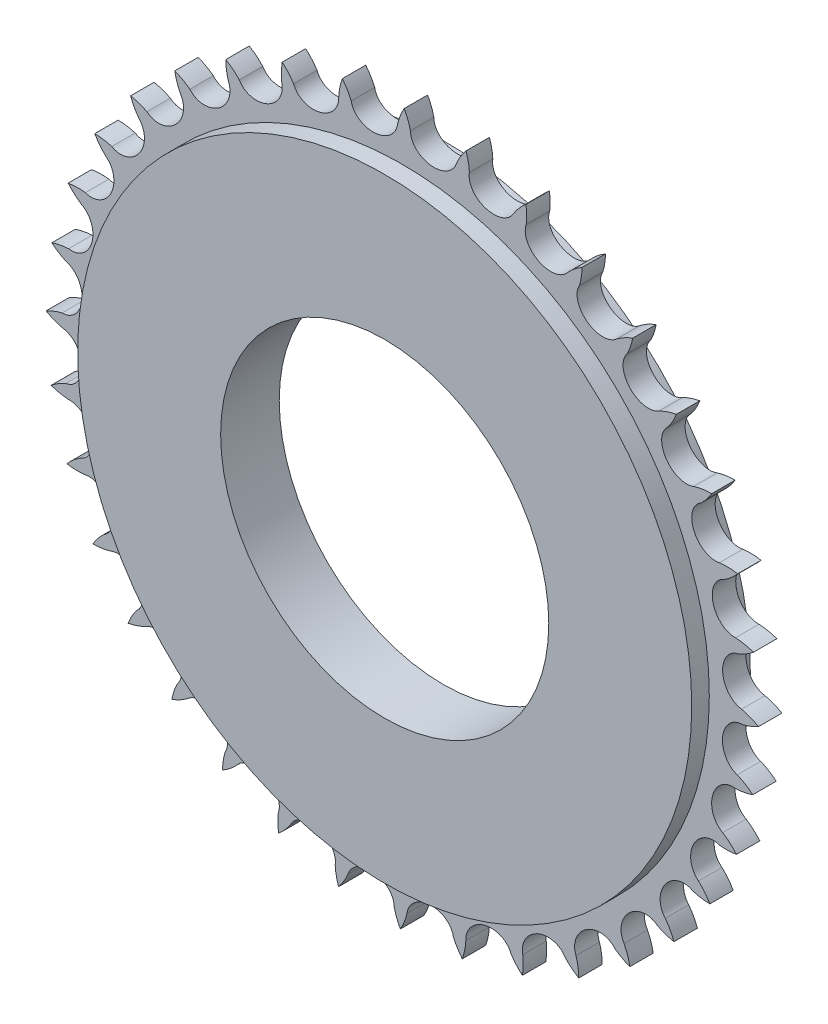
SolidWorks part; units mm, degrees
ref_plane "Front Plane" through (0, 0, 0) normal (0, 0, 1) x (1, 0, 0)
ref_plane "Top Plane" through (0, 0, 0) normal (0, 1, 0) x (1, 0, 0)
ref_plane "Right Plane" through (0, 0, 0) normal (1, 0, 0) x (0, 0, -1)
sketch "Sketch1" plane through (0, 0, 0) normal (0, 0, 1) x (1, 0, 0)
  arc A199 (14.3129, 71.1684) -> (13.5964, 74.7739) centre (1.3321, 70.4626) ccw
  arc A207 (1.7372, 72.5726) -> (0.4055, 75.9989) centre (-10.9239, 69.6235) ccw
  arc A208 (-1.0123, 72.3764) -> (0.4055, 75.9989) centre (11.6661, 69.503) cw
  arc A209 (11.5711, 71.4527) -> (13.5964, 74.7739) centre (23.5579, 66.4212) cw
  arc A210 (26.4537, 67.6018) -> (26.3742, 71.2769) centre (13.5475, 69.1608) ccw
  arc A211 (23.8029, 68.3578) -> (26.3742, 71.2769) centre (34.734, 61.3214) cw
  arc A212 (37.7908, 61.9811) -> (38.3506, 65.6143) centre (25.3514, 65.7576) ccw
  arc A213 (35.3115, 63.186) -> (38.3506, 65.6143) centre (44.8546, 54.3583) cw
  arc A214 (47.9795, 54.4772) -> (49.1618, 57.9579) centre (36.3849, 60.3564) ccw
  arc A215 (45.7472, 56.0943) -> (49.1618, 57.9579) centre (53.6124, 45.7435) cw
  arc A216 (56.7105, 45.318) -> (58.4792, 48.5406) centre (46.3129, 53.1213) ccw
  arc A217 (54.7929, 47.2982) -> (58.4792, 48.5406) centre (60.7412, 35.7389) cw
  arc A218 (63.7183, 34.7818) -> (66.0197, 37.6483) centre (54.8338, 44.2721) ccw
  arc A219 (62.1737, 37.0649) -> (66.0197, 37.6483) centre (66.0244, 24.6483) cw
  arc A220 (68.7901, 23.1889) -> (71.5543, 25.6122) centre (61.6885, 34.0777) ccw
  arc A221 (67.6654, 25.7055) -> (71.5543, 25.6122) centre (69.3015, 12.8088) cw
  arc A222 (71.7717, 10.8913) -> (74.9147, 12.7978) centre (66.6688, 22.8479) ccw
  arc A223 (71.1011, 13.565) -> (74.9147, 12.7978) centre (70.4728, 0.5802) cw
  arc A224 (72.5726, -1.7372) -> (75.9989, -0.4055) centre (69.6235, 10.9239) ccw
  arc A225 (72.3764, 1.0123) -> (75.9989, -0.4055) centre (69.503, -11.6661) cw
  arc A226 (71.1684, -14.3129) -> (74.7739, -13.5964) centre (70.4626, -1.3321) ccw
  arc A227 (71.4527, -11.5711) -> (74.7739, -13.5964) centre (66.4212, -23.5579) cw
  arc A228 (67.6018, -26.4537) -> (71.2769, -26.3742) centre (69.1608, -13.5475) ccw
  arc A229 (68.3578, -23.8029) -> (71.2769, -26.3742) centre (61.3214, -34.734) cw
  arc A230 (61.9811, -37.7908) -> (65.6143, -38.3506) centre (65.7576, -25.3514) ccw
  arc A231 (63.186, -35.3115) -> (65.6143, -38.3506) centre (54.3583, -44.8546) cw
  arc A232 (54.4772, -47.9795) -> (57.9579, -49.1618) centre (60.3564, -36.3849) ccw
  arc A233 (56.0943, -45.7472) -> (57.9579, -49.1618) centre (45.7435, -53.6124) cw
  arc A234 (45.318, -56.7105) -> (48.5406, -58.4792) centre (53.1213, -46.3129) ccw
  arc A235 (47.2982, -54.7929) -> (48.5406, -58.4792) centre (35.7389, -60.7412) cw
  arc A236 (34.7818, -63.7183) -> (37.6483, -66.0197) centre (44.2721, -54.8338) ccw
  arc A237 (37.0649, -62.1737) -> (37.6483, -66.0197) centre (24.6483, -66.0244) cw
  arc A238 (23.1889, -68.7901) -> (25.6122, -71.5543) centre (34.0777, -61.6885) ccw
  arc A239 (25.7055, -67.6654) -> (25.6122, -71.5543) centre (12.8088, -69.3015) cw
  arc A240 (10.8913, -71.7717) -> (12.7978, -74.9147) centre (22.8479, -66.6688) ccw
  arc A241 (13.565, -71.1011) -> (12.7978, -74.9147) centre (0.5802, -70.4728) cw
  arc A242 (-1.7372, -72.5726) -> (-0.4055, -75.9989) centre (10.9239, -69.6235) ccw
  arc A243 (1.0123, -72.3764) -> (-0.4055, -75.9989) centre (-11.6661, -69.503) cw
  arc A244 (-14.3129, -71.1684) -> (-13.5964, -74.7739) centre (-1.3321, -70.4626) ccw
  arc A245 (-11.5711, -71.4527) -> (-13.5964, -74.7739) centre (-23.5579, -66.4212) cw
  arc A246 (-26.4537, -67.6018) -> (-26.3742, -71.2769) centre (-13.5475, -69.1608) ccw
  arc A247 (-23.8029, -68.3578) -> (-26.3742, -71.2769) centre (-34.734, -61.3214) cw
  arc A248 (-37.7908, -61.9811) -> (-38.3506, -65.6143) centre (-25.3514, -65.7576) ccw
  arc A249 (-35.3115, -63.186) -> (-38.3506, -65.6143) centre (-44.8546, -54.3583) cw
  arc A250 (-47.9795, -54.4772) -> (-49.1618, -57.9579) centre (-36.3849, -60.3564) ccw
  arc A251 (-45.7472, -56.0943) -> (-49.1618, -57.9579) centre (-53.6124, -45.7435) cw
  arc A252 (-56.7105, -45.318) -> (-58.4792, -48.5406) centre (-46.3129, -53.1213) ccw
  arc A253 (-54.7929, -47.2982) -> (-58.4792, -48.5406) centre (-60.7412, -35.7389) cw
  arc A254 (-63.7183, -34.7818) -> (-66.0197, -37.6483) centre (-54.8338, -44.2721) ccw
  arc A255 (-62.1737, -37.0649) -> (-66.0197, -37.6483) centre (-66.0244, -24.6483) cw
  arc A256 (-68.7901, -23.1889) -> (-71.5543, -25.6122) centre (-61.6885, -34.0777) ccw
  arc A257 (-67.6654, -25.7055) -> (-71.5543, -25.6122) centre (-69.3015, -12.8088) cw
  arc A258 (-71.7717, -10.8913) -> (-74.9147, -12.7978) centre (-66.6688, -22.8479) ccw
  arc A259 (-71.1011, -13.565) -> (-74.9147, -12.7978) centre (-70.4728, -0.5802) cw
  arc A260 (-72.5726, 1.7372) -> (-75.9989, 0.4055) centre (-69.6235, -10.9239) ccw
  arc A261 (-72.3764, -1.0123) -> (-75.9989, 0.4055) centre (-69.503, 11.6661) cw
  arc A262 (-71.1684, 14.3129) -> (-74.7739, 13.5964) centre (-70.4626, 1.3321) ccw
  arc A263 (-71.4527, 11.5711) -> (-74.7739, 13.5964) centre (-66.4212, 23.5579) cw
  arc A264 (-67.6018, 26.4537) -> (-71.2769, 26.3742) centre (-69.1608, 13.5475) ccw
  arc A265 (-68.3578, 23.8029) -> (-71.2769, 26.3742) centre (-61.3214, 34.734) cw
  arc A266 (-61.9811, 37.7908) -> (-65.6143, 38.3506) centre (-65.7576, 25.3514) ccw
  arc A267 (-63.186, 35.3115) -> (-65.6143, 38.3506) centre (-54.3583, 44.8546) cw
  arc A268 (-54.4772, 47.9795) -> (-57.9579, 49.1618) centre (-60.3564, 36.3849) ccw
  arc A269 (-56.0943, 45.7472) -> (-57.9579, 49.1618) centre (-45.7435, 53.6124) cw
  arc A270 (-45.318, 56.7105) -> (-48.5406, 58.4792) centre (-53.1213, 46.3129) ccw
  arc A271 (-47.2982, 54.7929) -> (-48.5406, 58.4792) centre (-35.7389, 60.7412) cw
  arc A272 (-34.7818, 63.7183) -> (-37.6483, 66.0197) centre (-44.2721, 54.8338) ccw
  arc A273 (-37.0649, 62.1737) -> (-37.6483, 66.0197) centre (-24.6483, 66.0244) cw
  arc A274 (-23.1889, 68.7901) -> (-25.6122, 71.5543) centre (-34.0777, 61.6885) ccw
  arc A275 (-25.7055, 67.6654) -> (-25.6122, 71.5543) centre (-12.8088, 69.3015) cw
  arc A276 (-10.8913, 71.7717) -> (-12.7978, 74.9147) centre (-22.8479, 66.6688) ccw
  arc A277 (-13.565, 71.1011) -> (-12.7978, 74.9147) centre (-0.5802, 70.4728) cw
  circle A278 centre (0, 0) radius 35
  ellipse E0 centre (19.2322, 70.2739) end of major axis (14.3129, 71.1684) minor radius 4.25 (14.3129, 71.1684) -> (18.4719, 66.0925) ccw
  ellipse E1 centre (6.7371, 72.5459) end of major axis (11.7371, 72.5192) minor radius 4.25 (1.7372, 72.5726) -> (6.7145, 68.296) ccw
  ellipse E2 centre (6.7371, 72.5459) end of major axis (11.7371, 72.5192) minor radius 4.25 (6.7145, 68.296) -> (11.5711, 71.4527) ccw
  ellipse E3 centre (31.143, 65.8666) end of major axis (35.8323, 64.1315) minor radius 4.25 (26.4537, 67.6018) -> (29.6681, 61.8808) ccw
  ellipse E4 centre (19.2322, 70.2739) end of major axis (24.1516, 69.3794) minor radius 4.25 (18.4719, 66.0925) -> (23.8029, 68.3578) ccw
  ellipse E5 centre (-5.9627, 72.6137) end of major axis (-1.0341, 73.4556) minor radius 4.25 (-5.247, 68.4244) -> (-1.0123, 72.3764) ccw
  ellipse E6 centre (42.1075, 59.458) end of major axis (37.7908, 61.9811) minor radius 4.25 (37.7908, 61.9811) -> (39.9629, 55.7888) ccw
  ellipse E7 centre (31.143, 65.8666) end of major axis (35.8323, 64.1315) minor radius 4.25 (29.6681, 61.8808) -> (35.3115, 63.186) ccw
  ellipse E8 centre (51.7926, 51.2429) end of major axis (47.9795, 54.4772) minor radius 4.25 (47.9795, 54.4772) -> (49.0434, 48.0018) ccw
  ellipse E9 centre (42.1075, 59.458) end of major axis (46.4242, 56.935) minor radius 4.25 (39.9629, 55.7888) -> (45.7472, 56.0943) ccw
  ellipse E10 centre (59.9039, 41.4707) end of major axis (63.0974, 37.6234) minor radius 4.25 (56.7105, 45.318) -> (56.6337, 38.7562) ccw
  ellipse E11 centre (51.7926, 51.2429) end of major axis (55.6056, 48.0085) minor radius 4.25 (49.0434, 48.0018) -> (54.7929, 47.2982) ccw
  ellipse E12 centre (66.1952, 30.4384) end of major axis (63.7183, 34.7818) minor radius 4.25 (63.7183, 34.7818) -> (62.5033, 28.3331) ccw
  ellipse E13 centre (59.9039, 41.4707) end of major axis (63.0974, 37.6234) minor radius 4.25 (56.6337, 38.7562) -> (62.1737, 37.0649) ccw
  ellipse E14 centre (70.4751, 18.4813) end of major axis (68.7901, 23.1889) minor radius 4.25 (68.7901, 23.1889) -> (66.4737, 17.0491) ccw
  ellipse E15 centre (66.1952, 30.4384) end of major axis (68.672, 26.095) minor radius 4.25 (62.5033, 28.3331) -> (67.6654, 25.7055) ccw
  ellipse E16 centre (72.6137, 5.9627) end of major axis (73.4556, 1.0341) minor radius 4.25 (71.7717, 10.8913) -> (68.4244, 5.247) ccw
  ellipse E17 centre (70.4751, 18.4813) end of major axis (72.1601, 13.7738) minor radius 4.25 (66.4737, 17.0491) -> (71.1011, 13.565) ccw
  ellipse E18 centre (72.5459, -6.7371) end of major axis (72.5726, -1.7372) minor radius 4.25 (72.5726, -1.7372) -> (68.296, -6.7145) ccw
  ellipse E19 centre (72.6137, 5.9627) end of major axis (73.4556, 1.0341) minor radius 4.25 (68.4244, 5.247) -> (72.3764, 1.0123) ccw
  ellipse E20 centre (70.2739, -19.2322) end of major axis (71.1684, -14.3129) minor radius 4.25 (71.1684, -14.3129) -> (66.0925, -18.4719) ccw
  ellipse E21 centre (72.5459, -6.7371) end of major axis (72.5192, -11.7371) minor radius 4.25 (68.296, -6.7145) -> (71.4527, -11.5711) ccw
  ellipse E22 centre (65.8666, -31.143) end of major axis (67.6018, -26.4537) minor radius 4.25 (67.6018, -26.4537) -> (61.8808, -29.6681) ccw
  ellipse E23 centre (70.2739, -19.2322) end of major axis (69.3794, -24.1516) minor radius 4.25 (66.0925, -18.4719) -> (68.3578, -23.8029) ccw
  ellipse E24 centre (59.458, -42.1075) end of major axis (61.9811, -37.7908) minor radius 4.25 (61.9811, -37.7908) -> (55.7888, -39.9629) ccw
  ellipse E25 centre (65.8666, -31.143) end of major axis (64.1315, -35.8323) minor radius 4.25 (61.8808, -29.6681) -> (63.186, -35.3115) ccw
  ellipse E26 centre (51.2429, -51.7926) end of major axis (54.4772, -47.9795) minor radius 4.25 (54.4772, -47.9795) -> (48.0018, -49.0434) ccw
  ellipse E27 centre (59.458, -42.1075) end of major axis (56.935, -46.4242) minor radius 4.25 (55.7888, -39.9629) -> (56.0943, -45.7472) ccw
  ellipse E28 centre (41.4707, -59.9039) end of major axis (37.6234, -63.0974) minor radius 4.25 (45.318, -56.7105) -> (38.7562, -56.6337) ccw
  ellipse E29 centre (51.2429, -51.7926) end of major axis (48.0085, -55.6056) minor radius 4.25 (48.0018, -49.0434) -> (47.2982, -54.7929) ccw
  ellipse E30 centre (30.4384, -66.1952) end of major axis (26.095, -68.672) minor radius 4.25 (34.7818, -63.7183) -> (28.3331, -62.5033) ccw
  ellipse E31 centre (41.4707, -59.9039) end of major axis (37.6234, -63.0974) minor radius 4.25 (38.7562, -56.6337) -> (37.0649, -62.1737) ccw
  ellipse E32 centre (18.4813, -70.4751) end of major axis (23.1889, -68.7901) minor radius 4.25 (23.1889, -68.7901) -> (17.0491, -66.4737) ccw
  ellipse E33 centre (30.4384, -66.1952) end of major axis (34.7818, -63.7183) minor radius 4.25 (28.3331, -62.5033) -> (25.7055, -67.6654) ccw
  ellipse E34 centre (5.9627, -72.6137) end of major axis (1.0341, -73.4556) minor radius 4.25 (10.8913, -71.7717) -> (5.247, -68.4244) ccw
  ellipse E35 centre (18.4813, -70.4751) end of major axis (13.7738, -72.1601) minor radius 4.25 (17.0491, -66.4737) -> (13.565, -71.1011) ccw
  ellipse E36 centre (-6.7371, -72.5459) end of major axis (-1.7372, -72.5726) minor radius 4.25 (-1.7372, -72.5726) -> (-6.7145, -68.296) ccw
  ellipse E37 centre (5.9627, -72.6137) end of major axis (1.0341, -73.4556) minor radius 4.25 (5.247, -68.4244) -> (1.0123, -72.3764) ccw
  ellipse E38 centre (-19.2322, -70.2739) end of major axis (-14.3129, -71.1684) minor radius 4.25 (-14.3129, -71.1684) -> (-18.4719, -66.0925) ccw
  ellipse E39 centre (-6.7371, -72.5459) end of major axis (-11.7371, -72.5192) minor radius 4.25 (-6.7145, -68.296) -> (-11.5711, -71.4527) ccw
  ellipse E40 centre (-31.143, -65.8666) end of major axis (-26.4537, -67.6018) minor radius 4.25 (-26.4537, -67.6018) -> (-29.6681, -61.8808) ccw
  ellipse E41 centre (-19.2322, -70.2739) end of major axis (-24.1516, -69.3794) minor radius 4.25 (-18.4719, -66.0925) -> (-23.8029, -68.3578) ccw
  ellipse E42 centre (-42.1075, -59.458) end of major axis (-37.7908, -61.9811) minor radius 4.25 (-37.7908, -61.9811) -> (-39.9629, -55.7888) ccw
  ellipse E43 centre (-31.143, -65.8666) end of major axis (-35.8323, -64.1315) minor radius 4.25 (-29.6681, -61.8808) -> (-35.3115, -63.186) ccw
  ellipse E44 centre (-51.7926, -51.2429) end of major axis (-47.9795, -54.4772) minor radius 4.25 (-47.9795, -54.4772) -> (-49.0434, -48.0018) ccw
  ellipse E45 centre (-42.1075, -59.458) end of major axis (-46.4242, -56.935) minor radius 4.25 (-39.9629, -55.7888) -> (-45.7472, -56.0943) ccw
  ellipse E46 centre (-59.9039, -41.4707) end of major axis (-63.0974, -37.6234) minor radius 4.25 (-56.7105, -45.318) -> (-56.6337, -38.7562) ccw
  ellipse E47 centre (-51.7926, -51.2429) end of major axis (-47.9795, -54.4772) minor radius 4.25 (-49.0434, -48.0018) -> (-54.7929, -47.2982) ccw
  ellipse E48 centre (-66.1952, -30.4384) end of major axis (-63.7183, -34.7818) minor radius 4.25 (-63.7183, -34.7818) -> (-62.5033, -28.3331) ccw
  ellipse E49 centre (-59.9039, -41.4707) end of major axis (-63.0974, -37.6234) minor radius 4.25 (-56.6337, -38.7562) -> (-62.1737, -37.0649) ccw
  ellipse E50 centre (-70.4751, -18.4813) end of major axis (-68.7901, -23.1889) minor radius 4.25 (-68.7901, -23.1889) -> (-66.4737, -17.0491) ccw
  ellipse E51 centre (-66.1952, -30.4384) end of major axis (-68.672, -26.095) minor radius 4.25 (-62.5033, -28.3331) -> (-67.6654, -25.7055) ccw
  ellipse E52 centre (-72.6137, -5.9627) end of major axis (-71.7717, -10.8913) minor radius 4.25 (-71.7717, -10.8913) -> (-68.4244, -5.247) ccw
  ellipse E53 centre (-70.4751, -18.4813) end of major axis (-68.7901, -23.1889) minor radius 4.25 (-66.4737, -17.0491) -> (-71.1011, -13.565) ccw
  ellipse E54 centre (-72.5459, 6.7371) end of major axis (-72.5192, 11.7371) minor radius 4.25 (-72.5726, 1.7372) -> (-68.296, 6.7145) ccw
  ellipse E55 centre (-72.6137, -5.9627) end of major axis (-71.7717, -10.8913) minor radius 4.25 (-68.4244, -5.247) -> (-72.3764, -1.0123) ccw
  ellipse E56 centre (-70.2739, 19.2322) end of major axis (-71.1684, 14.3129) minor radius 4.25 (-71.1684, 14.3129) -> (-66.0925, 18.4719) ccw
  ellipse E57 centre (-72.5459, 6.7371) end of major axis (-72.5192, 11.7371) minor radius 4.25 (-68.296, 6.7145) -> (-71.4527, 11.5711) ccw
  ellipse E58 centre (-65.8666, 31.143) end of major axis (-67.6018, 26.4537) minor radius 4.25 (-67.6018, 26.4537) -> (-61.8808, 29.6681) ccw
  ellipse E59 centre (-70.2739, 19.2322) end of major axis (-69.3794, 24.1516) minor radius 4.25 (-66.0925, 18.4719) -> (-68.3578, 23.8029) ccw
  ellipse E60 centre (-59.458, 42.1075) end of major axis (-61.9811, 37.7908) minor radius 4.25 (-61.9811, 37.7908) -> (-55.7888, 39.9629) ccw
  ellipse E61 centre (-65.8666, 31.143) end of major axis (-67.6018, 26.4537) minor radius 4.25 (-61.8808, 29.6681) -> (-63.186, 35.3115) ccw
  ellipse E62 centre (-51.2429, 51.7926) end of major axis (-54.4772, 47.9795) minor radius 4.25 (-54.4772, 47.9795) -> (-48.0018, 49.0434) ccw
  ellipse E63 centre (-59.458, 42.1075) end of major axis (-56.935, 46.4242) minor radius 4.25 (-55.7888, 39.9629) -> (-56.0943, 45.7472) ccw
  ellipse E64 centre (-41.4707, 59.9039) end of major axis (-37.6234, 63.0974) minor radius 4.25 (-45.318, 56.7105) -> (-38.7562, 56.6337) ccw
  ellipse E65 centre (-51.2429, 51.7926) end of major axis (-48.0085, 55.6056) minor radius 4.25 (-48.0018, 49.0434) -> (-47.2982, 54.7929) ccw
  ellipse E66 centre (-30.4384, 66.1952) end of major axis (-34.7818, 63.7183) minor radius 4.25 (-34.7818, 63.7183) -> (-28.3331, 62.5033) ccw
  ellipse E67 centre (-41.4707, 59.9039) end of major axis (-37.6234, 63.0974) minor radius 4.25 (-38.7562, 56.6337) -> (-37.0649, 62.1737) ccw
  ellipse E68 centre (-18.4813, 70.4751) end of major axis (-23.1889, 68.7901) minor radius 4.25 (-23.1889, 68.7901) -> (-17.0491, 66.4737) ccw
  ellipse E69 centre (-30.4384, 66.1952) end of major axis (-26.095, 68.672) minor radius 4.25 (-28.3331, 62.5033) -> (-25.7055, 67.6654) ccw
  ellipse E70 centre (-5.9627, 72.6137) end of major axis (-10.8913, 71.7717) minor radius 4.25 (-10.8913, 71.7717) -> (-5.247, 68.4244) ccw
  ellipse E71 centre (-18.4813, 70.4751) end of major axis (-13.7738, 72.1601) minor radius 4.25 (-17.0491, 66.4737) -> (-13.565, 71.1011) ccw
  dimension "D1" = 36
extrude "Boss-Extrude1" add sketch "Sketch1" along normal mid plane 5
sketch "Sketch2" plane through (0, 0, 0) normal (0, 0, 1) x (1, 0, 0)
  circle A0 centre (0, 0) radius 35
  circle A1 centre (0, 0) radius 65.5
extrude "Boss-Extrude2" add sketch "Sketch2" along normal mid plane 12.5
